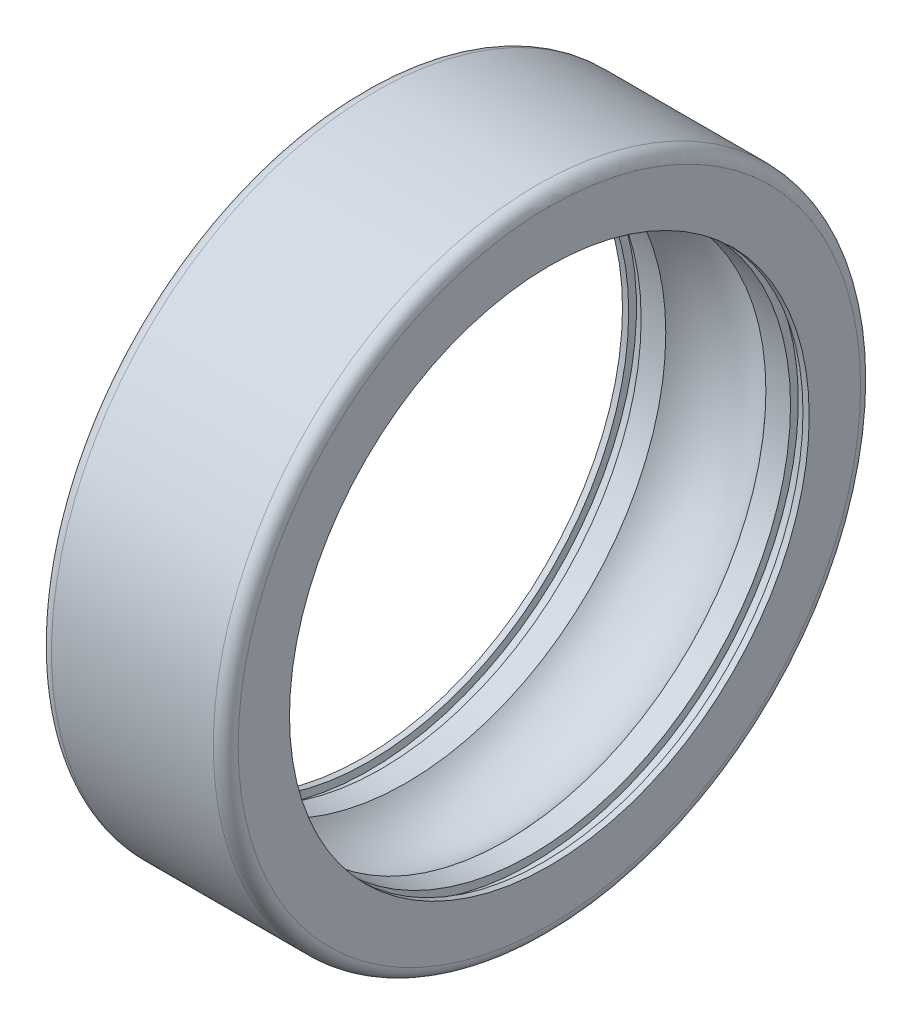
SolidWorks part; units mm, degrees
material "AISI 304"
ref_plane "Front Plane" through (0, 0, 0) normal (0, 0, 1) x (1, 0, 0)
ref_plane "Top Plane" through (0, 0, 0) normal (0, 1, 0) x (1, 0, 0)
ref_plane "Right Plane" through (0, 0, 0) normal (1, 0, 0) x (0, 0, -1)
sketch "Sketch1" plane through (0, 0, 0) normal (1, 0, 0) x (0, 0, -1)
  circle A0 centre (0, 0) radius 26
  circle A1 centre (0, 0) radius 20.875
  dimension "D1" = 52
  dimension "D2" = 41.75
extrude "Boss-Extrude1" add sketch "Sketch1" along normal mid plane 15
sketch "Sketch2" plane through (0, 0, 0) normal (0, 0, 1) x (1, 0, 0)
  line L1 (7.5, 20.875) -> (-7.5, 20.875) construction
  line L2 (0, 0) -> (27.1397, 0) construction
  circle A0 centre (0, 17.5) radius 5.25
  dimension "D1" = 10.5
  dimension "D2" = 1.875
revolve "Cut-Revolve1" cut sketch "Sketch2" angle 360 about L2
sketch "Sketch3" plane through (0, 0, 0) normal (0, 0, 1) x (1, 0, 0)
  line L0 (-4.0214, 20.875) -> (-7.5, 20.875) construction
  line L1 (-7, 20.875) -> (-6, 20.875)
  line L2 (-7, 20.875) -> (-7, 21.5)
  line L3 (-7, 21.5) -> (-6, 21.5)
  line L4 (-6, 20.875) -> (-6, 21.5)
  line L5 (-7.5, 26) -> (-7.5, -26) construction
  line L6 (0, 0) -> (17.6831, 0) construction
  line L7 (0, 0) -> (0, 12.3065) construction
  line L8 (6, 20.875) -> (6, 21.5)
  line L9 (7, 21.5) -> (6, 21.5)
  line L10 (7, 20.875) -> (7, 21.5)
  line L11 (7, 20.875) -> (6, 20.875)
  point P8 (-6.5, 20.875)
  dimension "D1" = 0.5
  dimension "D2" = 1
  dimension "D3" = 0.625
revolve "Cut-Revolve2" cut sketch "Sketch3" angle 360 about L6
fillet "Fillet1" radius 1 2 edges at (-7.5, 0, -26) (7.5, 0, -26)
